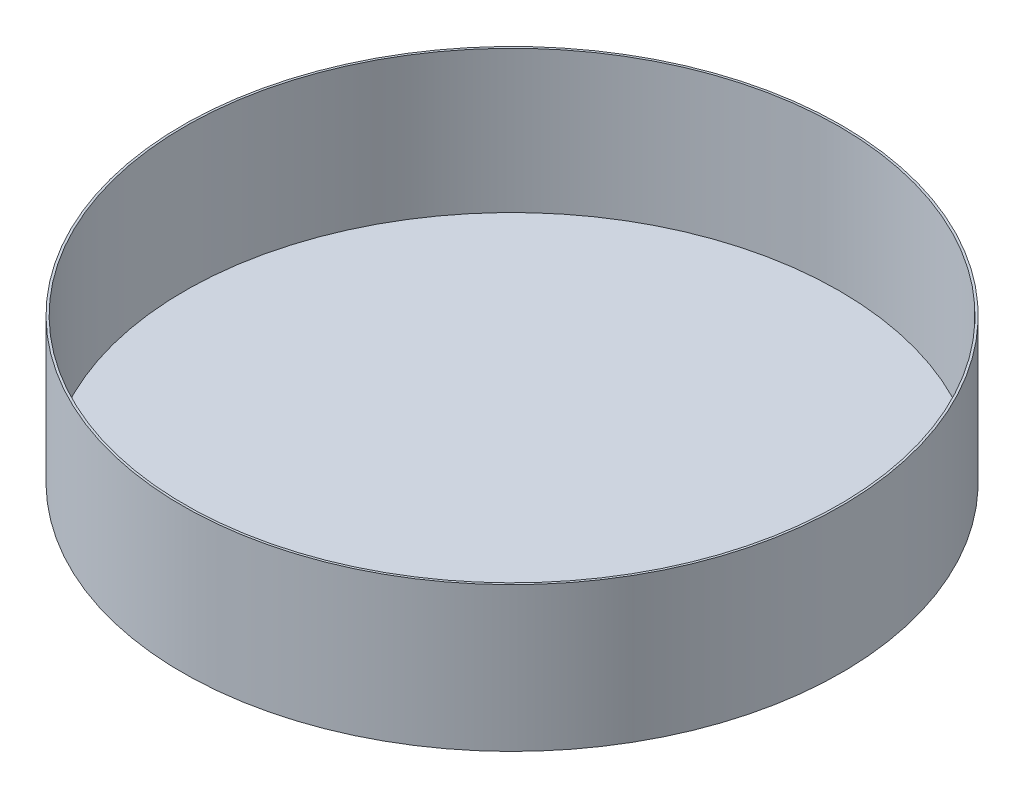
SolidWorks part; units mm, degrees
material "Alumina"
ref_plane "Front Plane" through (0, 0, 0) normal (0, 0, 1) x (1, 0, 0)
ref_plane "Top Plane" through (0, 0, 0) normal (0, 1, 0) x (1, 0, 0)
ref_plane "Right Plane" through (0, 0, 0) normal (1, 0, 0) x (0, 0, -1)
sketch "Sketch1" plane through (0, 0, 0) normal (0, 0, 1) x (1, 0, 0)
  line L0 (0, 0) -> (0, 2000) construction
  line L1 (0, 0) -> (1495.54, 0)
  line L3 (1495.54, 0) -> (1495.54, 650)
  line L5 (0, 0) -> (0, -10) construction
  line L6 (1495.54, 0) -> (1505.54, 0) construction
  line L7 (1505.54, 0) -> (1505.54, -10) construction
  line L8 (0, -10) -> (1505.54, -10)
  line L9 (1505.54, -10) -> (1505.54, 650)
  line L10 (0, 2000) -> (0, 2010) construction
  line L11 (598.217, 2000) -> (598.217, 2010) construction
  line L13 (1046.8785, 1325) -> (1055.2066, 1330.5356) construction
  line L15 (610.2245, 2000) -> (598.217, 2010)
  line L17 (1495.54, 668.065) -> (1505.54, 650)
  line L18 (0, 2010) -> (0, 2000)
  line L19 (0, 0) -> (0, -10)
  line L20 (1505.54, 650) -> (1495.54, 650)
revolve "Revolve1" add sketch "Sketch1" angle 360 about L0
